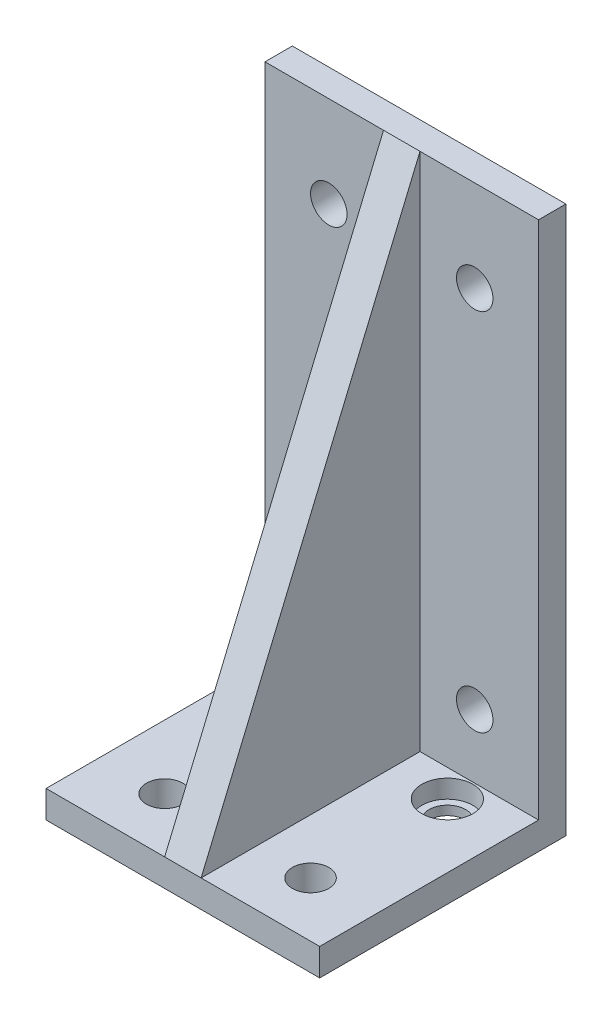
SolidWorks part; units mm, degrees
ref_plane "Front Plane" through (0, 0, 0) normal (0, 0, 1) x (1, 0, 0)
ref_plane "Top Plane" through (0, 0, 0) normal (0, 1, 0) x (1, 0, 0)
ref_plane "Right Plane" through (0, 0, 0) normal (1, 0, 0) x (0, 0, -1)
sketch "Sketch1" plane through (0, 0, 0) normal (0, 0, 1) x (1, 0, 0)
  line L0 (0, 30) -> (0, -30) construction
  line L1 (15, 30) -> (-15, 30)
  line L2 (15, 30) -> (15, -30)
  line L3 (15, -30) -> (-15, -30)
  line L4 (-15, 30) -> (-15, -30)
  line L5 (15, 30) -> (-15, -30) construction
  line L6 (15, -30) -> (-15, 30) construction
  line L7 (15, 0) -> (-15, 0) construction
  circle A0 centre (8, 20) radius 2
  circle A1 centre (8, -20) radius 2
  circle A2 centre (-8, 20) radius 2
  circle A3 centre (-8, -20) radius 2
  point P0 (0, 0)
  dimension "D3" = 4
  dimension "D1" = 60
  dimension "D2" = 30
  dimension "D4" = 8
  dimension "D5" = 20
extrude "Boss-Extrude1" add sketch "Sketch1" along normal blind 3
sketch "Sketch2" plane through (0, 0, 0) normal (1, 0, 0) x (0, 0, -1)
  line L1 (-3, -30) -> (-27, -30)
  line L2 (-3, -30) -> (-3, -27)
  line L3 (-3, -27) -> (-27, -27)
  line L4 (-27, -30) -> (-27, -27)
  dimension "D1" = 3
  dimension "D2" = 24
extrude "Boss-Extrude2" add sketch "Sketch2" along normal mid plane 30
sketch "Sketch3" plane through (0, -27, 0) normal (0, 1, 0) x (1, 0, 0)
  line L0 (0, 0) -> (0, -27) construction
  line L1 (15, -27) -> (-15, -27) construction
  line L2 (15, -3) -> (-15, -3) construction
  circle A0 centre (-8, -6) radius 2
  circle A1 centre (8, -6) radius 2
  circle A2 centre (-8, -21) radius 2
  circle A3 centre (8, -21) radius 2
  dimension "D1" = 4
  dimension "D4" = 4
  dimension "D5" = 4
  dimension "D2" = 3
  dimension "D3" = 8
  dimension "D6" = 15
  dimension "D7" = 15
extrude "Cut-Extrude1" cut sketch "Sketch3" against normal through all
sketch "Sketch4" plane through (0, -27, 0) normal (0, 1, 0) x (1, 0, 0)
  circle A2 centre (-8, -6) radius 2.8
  circle A3 centre (8, -6) radius 2.8
  dimension "D1" = 5.6
sketch "Sketch5" plane through (0, 0, 3) normal (0, 0, 1) x (1, 0, 0)
  circle A0 centre (-8, -20) radius 2.8
  circle A1 centre (8, -20) radius 2.8
  dimension "D1" = 5.6
sketch "Sketch6" plane through (0, 0, 0) normal (1, 0, 0) x (0, 0, -1)
  line L0 (-3, 30) -> (-27, -27)
  line L1 (-27, -27) -> (-3, -27)
  line L2 (-3, -27) -> (-3, 30)
extrude "Boss-Extrude3" add sketch "Sketch6" along normal mid plane 4
extrude "Cut-Extrude2" cut sketch "Sketch4" against normal blind 2
